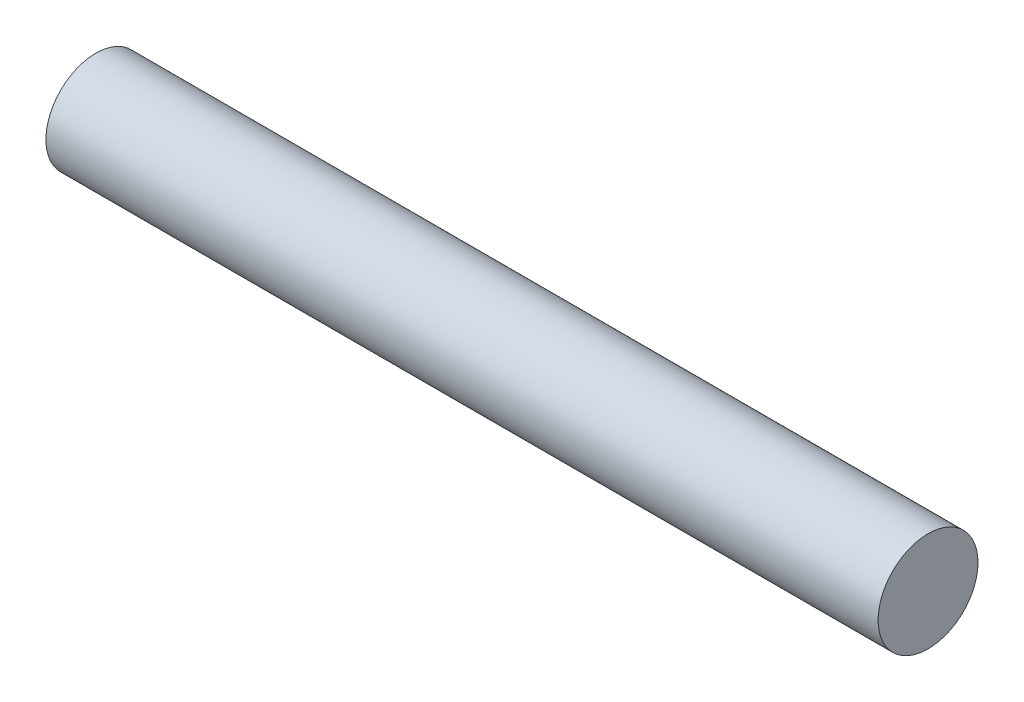
SolidWorks part; units mm, degrees
ref_plane "Front Plane" through (0, 0, 0) normal (0, 0, 1) x (1, 0, 0)
ref_plane "Top Plane" through (0, 0, 0) normal (0, 1, 0) x (1, 0, 0)
ref_plane "Right Plane" through (0, 0, 0) normal (1, 0, 0) x (0, 0, -1)
sketch "Sketch1" plane through (0, 0, 0) normal (1, 0, 0) x (0, 0, -1)
  circle A0 centre (0, 0) radius 0.75
  dimension "D1" = 1.5
extrude "Boss-Extrude1" add sketch "Sketch1" along normal mid plane 12.5
